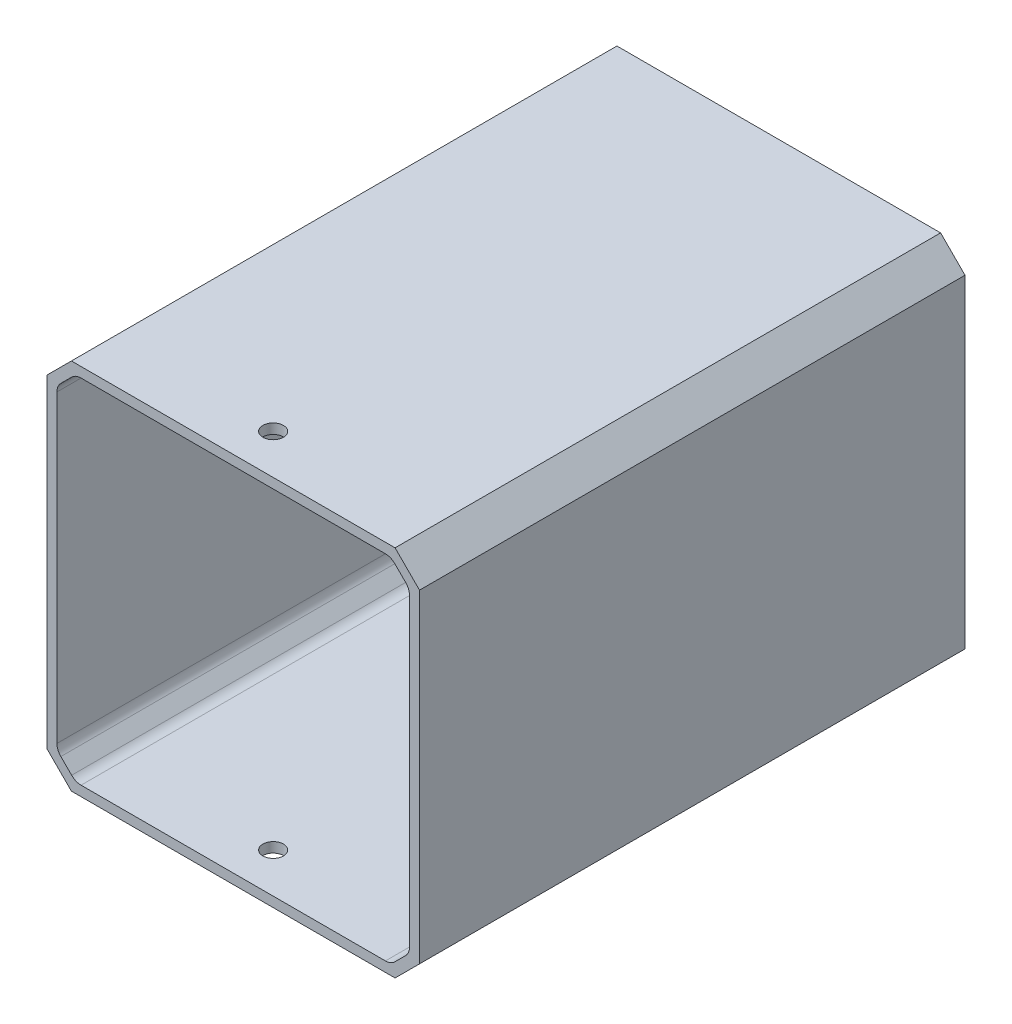
SolidWorks part; units mm, degrees
ref_plane "Plan de face" through (0, 0, 0) normal (0, 0, 1) x (1, 0, 0)
ref_plane "Plan de dessus" through (0, 0, 0) normal (0, 1, 0) x (1, 0, 0)
ref_plane "Plan de droite" through (0, 0, 0) normal (1, 0, 0) x (0, 0, -1)
sketch "Esquisse1" plane through (0, 0, 0) normal (0, 0, 1) x (1, 0, 0)
  line L0 (28.2843, 28.2843) -> (-28.2843, -28.2843) construction
  line L1 (-24.3259, 28) -> (24.3259, 28)
  line L2 (-28, 24.3259) -> (-28, -24.3259)
  line L3 (-24.3259, -28) -> (24.3259, -28)
  line L4 (28, 24.3259) -> (28, -24.3259)
  line L5 (28, 24.3259) -> (24.3259, 28)
  line L6 (24.3259, -28) -> (28, -24.3259)
  line L7 (-28, -24.3259) -> (-24.3259, -28)
  line L8 (-24.3259, 28) -> (-28, 24.3259)
  circle A0 centre (0, 0) radius 40 construction
  circle A4 centre (0, 0) radius 11.15
  point P1 (26.163, 26.163)
  point P4 (0, 0)
  point P21 (0, 0)
  dimension "D1" = 22.3
  dimension "D2" = 3
  dimension "D3" = 4
  dimension "D4" = 56
extrude "Boss.-Extru.1" add sketch "Esquisse1" along normal blind 2
sketch "Esquisse2" plane through (0, 0, 2) normal (0, 0, 1) x (1, 0, 0)
  line L4 (-28, 24.3259) -> (-28, -24.3259)
  line L5 (-24.3259, -28) -> (24.3259, -28)
  line L6 (28, -24.3259) -> (28, 24.3259)
  line L7 (24.3259, 28) -> (-24.3259, 28)
  line L8 (-28, 24.3259) -> (-28, -24.3259)
  line L9 (-24.3259, -28) -> (24.3259, -28)
  line L10 (28, -24.3259) -> (28, 24.3259)
  line L11 (24.3259, 28) -> (-24.3259, 28)
  line L16 (-26.5, 23.7046) -> (-26.5, -23.7046)
  line L17 (-23.7046, -26.5) -> (23.7046, -26.5)
  line L18 (26.5, -23.7046) -> (26.5, 23.7046)
  line L19 (23.7046, 26.5) -> (-23.7046, 26.5)
  line L20 (-26.5, 23.7046) -> (-26.5, -23.7046)
  line L21 (-23.7046, -26.5) -> (23.7046, -26.5)
  line L22 (26.5, -23.7046) -> (26.5, 23.7046)
  line L23 (23.7046, 26.5) -> (-23.7046, 26.5)
  line L24 (28, 24.3259) -> (24.3259, 28)
  line L25 (28, 24.3259) -> (24.3259, 28)
  line L26 (-24.3259, 28) -> (-28, 24.3259)
  line L27 (-24.3259, 28) -> (-28, 24.3259)
  line L28 (-28, -24.3259) -> (-24.3259, -28)
  line L29 (-28, -24.3259) -> (-24.3259, -28)
  line L30 (24.3259, -28) -> (28, -24.3259)
  line L31 (24.3259, -28) -> (28, -24.3259)
  line L32 (26.5, 23.7046) -> (23.7046, 26.5)
  line L33 (26.5, 23.7046) -> (23.7046, 26.5)
  line L34 (-23.7046, 26.5) -> (-26.5, 23.7046)
  line L35 (-23.7046, 26.5) -> (-26.5, 23.7046)
  line L36 (-26.5, -23.7046) -> (-23.7046, -26.5)
  line L37 (-26.5, -23.7046) -> (-23.7046, -26.5)
  line L38 (23.7046, -26.5) -> (26.5, -23.7046)
  line L39 (23.7046, -26.5) -> (26.5, -23.7046)
  dimension "D1" = 0
  dimension "D2" = 1.5
extrude "Boss.-Extru.2" add sketch "Esquisse2" along normal blind 80
sketch "Esquisse3" plane through (0, 0, 0) normal (0, 0, -1) x (-1, 0, 0)
  line L0 (-28, -20) -> (-28, 20)
  line L1 (-28, -24.3259) -> (-28, 24.3259) construction
  line L2 (-28, 20) -> (-35.5, 12.5)
  line L3 (-35.5, 12.5) -> (-35.5, -12.5)
  line L4 (-35.5, -12.5) -> (-28, -20)
  line L5 (-35.5, 0) -> (-28, 0) construction
  line L6 (-31.75, 3.1754) -> (-34.5, 1.5877)
  line L7 (-34.5, 1.5877) -> (-34.5, -1.5877)
  line L8 (-34.5, -1.5877) -> (-31.75, -3.1754)
  line L9 (-31.75, -3.1754) -> (-29, -1.5877)
  line L10 (-29, -1.5877) -> (-29, 1.5877)
  line L11 (-29, 1.5877) -> (-31.75, 3.1754)
  circle A0 centre (-31.75, 0) radius 2.75 construction
  point P4 (-28, 0)
  point P20 (-31.75, 0)
  dimension "D1" = 45
  dimension "D2" = 45
  dimension "D3" = 40
  dimension "D4" = 25
  dimension "D5" = 5.5
extrude "Boss.-Extru.3" add sketch "Esquisse3" against normal blind 2.3
sketch "Esquisse4" plane through (0, 28, 0) normal (0, 1, 0) x (1, 0, 0)
  circle A0 centre (0, -76) radius 1.55 construction
  circle A1 centre (0, -76) radius 1.55
extrude "Enlèv. mat.-Extru.1" cut sketch "Esquisse4" against normal through all both and the other way through all
sketch "Esquisse5" plane through (0, 0, 2) normal (0, 0, 1) x (1, 0, 0)
  line L1 (-10.8281, -1.05) -> (-12.1, -1.05)
  line L3 (-10.8281, 1.05) -> (-12.1, 1.05)
  line L4 (-12.1, -1.05) -> (-12.1, 1.05)
  line L6 (-10.8281, -1.05) -> (-9.6, -1.05)
  line L7 (-9.6, -1.05) -> (-9.6, 1.05)
  line L8 (-9.6, 1.05) -> (-10.8281, 1.05)
  line L9 (-10.8281, -1.05) -> (-9.6, -1.05)
  line L10 (-9.6, -1.05) -> (-9.6, 1.05)
  line L11 (-9.6, 1.05) -> (-10.8281, 1.05)
  dimension "D2" = 2.5
  dimension "D1" = 0.2
extrude "Boss.-Extru.4" add sketch "Esquisse5" against normal up to surface (2 mm away) up to face at (10.5833, 0, 0)
sketch "Esquisse6" plane through (0, 0, 2.3) normal (0, 0, 1) x (1, 0, 0)
  line L4 (28, -20) -> (35.5, -12.5)
  line L5 (35.5, -12.5) -> (35.5, 12.5)
  line L6 (35.5, 12.5) -> (28, 20)
  line L7 (28, 20) -> (28, -20)
  line L8 (28, -20) -> (35.5, -12.5)
  line L9 (35.5, -12.5) -> (35.5, 12.5)
  line L10 (35.5, 12.5) -> (28, 20)
  line L11 (28, 20) -> (28, -20)
  dimension "D1" = 0
extrude "Enlèv. mat.-Extru.2" cut sketch "Esquisse6" against normal blind 10
fillet "Congé1" radius 2 8 edges at (23.7046, -26.5, 42) (26.5, -23.7046, 42) (-23.7046, -26.5, 42) (-26.5, -23.7046, 42) (26.5, 23.7046, 42) (23.7046, 26.5, 42) (-23.7046, 26.5, 42) (-26.5, 23.7046, 42)
